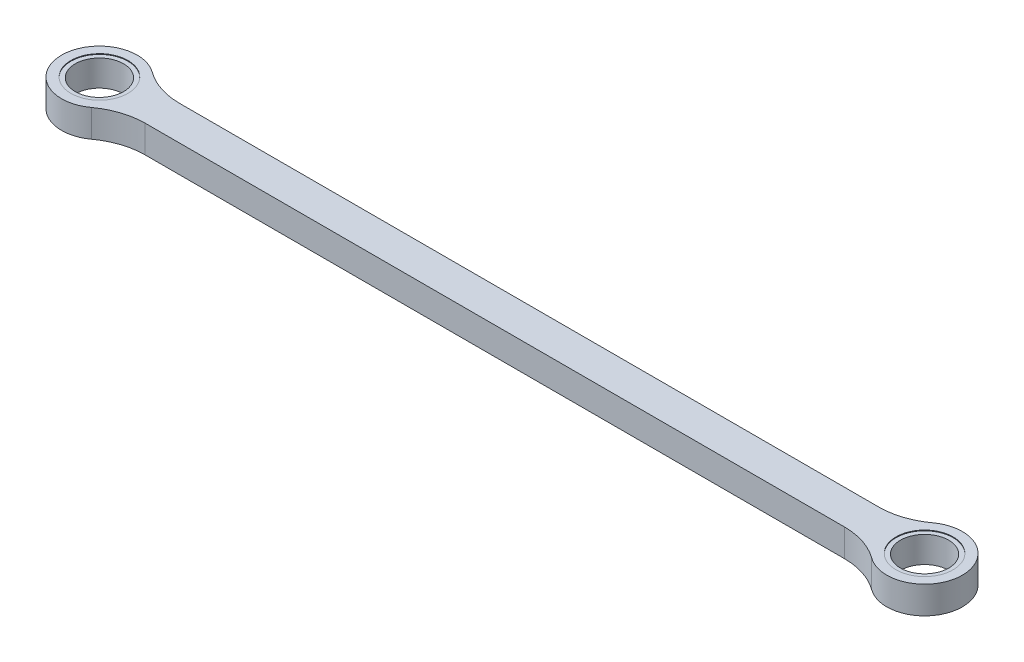
SolidWorks part; units mm, degrees
material "6061 合金"
ref_plane "前视基准面" through (0, 0, 0) normal (0, 0, 1) x (1, 0, 0)
ref_plane "上视基准面" through (0, 0, 0) normal (0, 1, 0) x (1, 0, 0)
ref_plane "右视基准面" through (0, 0, 0) normal (1, 0, 0) x (0, 0, -1)
other "Configuration Table"
sketch "草图1" plane through (0, 0, 0) normal (0, 1, 0) x (1, 0, 0)
  line L0 (0, 0) -> (120, 0) construction
  line L2 (4.899, 2.5) -> (115.101, 2.5)
  line L3 (4.899, 2.5) -> (4.899, -2.5) construction
  line L4 (4.899, -2.5) -> (115.101, -2.5)
  line L5 (115.101, 2.5) -> (115.101, -2.5) construction
  line L6 (60, -2.5) -> (60, 2.5) construction
  line L7 (4.899, 0) -> (115.101, 0) construction
  circle A0 centre (0, 0) radius 5.5 construction
  circle A1 centre (120, 0) radius 5.5 construction
  circle A2 centre (0, 0) radius 3.515
  circle A3 centre (120, 0) radius 3.515
  arc A4 (4.899, 2.5) -> (4.899, -2.5) centre (0, 0) ccw
  arc A5 (115.101, 2.5) -> (115.101, -2.5) centre (120, 0) cw
  point P7 (60, 0)
  dimension "D1" = 11
  dimension "D3" = 11
  dimension "D4" = 7.03
  dimension "D5" = 7.03
  dimension "D2" = 120
  dimension "D6" = 5
extrude "凸台-拉伸1" add sketch "草图1" along normal blind 4
fillet "圆角1" radius 10 4 edges at (115.101, 2, 2.5) (115.101, 2, -2.5) (4.899, 2, 2.5) (4.899, 2, -2.5)
sketch "草图2" plane through (0, 4, 0) normal (0, 1, 0) x (1, 0, 0)
  line L0 (110.8348, 2.5) -> (9.1652, 2.5) construction
  line L1 (9.1652, -2.5) -> (110.8348, -2.5) construction
  line L2 (60, 2.5) -> (60, -2.5) construction
  line L3 (110, 0) -> (10, 0) construction
  line L4 (110, -1.25) -> (10, -1.25)
  line L5 (110, 1.25) -> (10, 1.25)
  arc A6 (110, -1.25) -> (110, 1.25) centre (110, 0) ccw
  arc A7 (10, 1.25) -> (10, -1.25) centre (10, 0) ccw
  point P5 (60, 0)
  dimension "D1" = 50
  dimension "D2" = 2.5
extrude "切除-拉伸1" [suppressed] cut sketch "草图2" against normal blind 2
chamfer "倒角1" [suppressed] distance 0.5 angle 45
sketch "草图3" plane through (0, 4, 0) normal (0, 1, 0) x (1, 0, 0)
  circle A0 centre (0, 0) radius 4.15
  circle A1 centre (120, 0) radius 4.15
  dimension "D1" = 8.3
  dimension "D2" = 8.3
extrude "切除-拉伸2" cut sketch "草图3" against normal blind 0.1
sketch "草图4" plane through (0, 0, 0) normal (0, -1, 0) x (1, 0, 0)
  circle A0 centre (0, 0) radius 4.15
  circle A1 centre (120, 0) radius 4.15
  dimension "D1" = 8.3
  dimension "D2" = 8.3
extrude "切除-拉伸3" cut sketch "草图4" against normal blind 0.1
